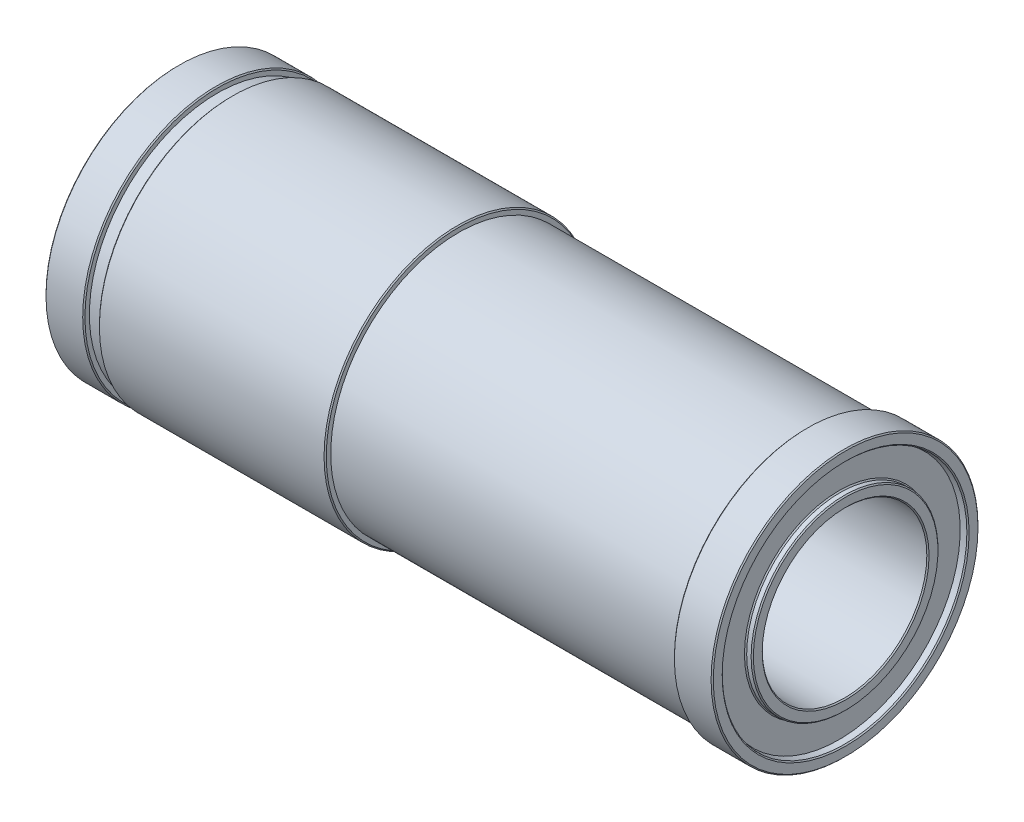
SolidWorks part; units mm, degrees
ref_plane "Front" through (0, 0, 0) normal (0, 0, 1) x (1, 0, 0)
ref_plane "Top" through (0, 0, 0) normal (0, 1, 0) x (1, 0, 0)
ref_plane "Right" through (0, 0, 0) normal (1, 0, 0) x (0, 0, -1)
sketch "Эскиз3" plane through (0, 0, 0) normal (0, 0, 1) x (1, 0, 0)
  line L0 (25.2, 8.9) -> (25.1, 9)
  line L1 (25.1, 9) -> (4.9, 9)
  line L2 (4.9, 9) -> (4.8, 8.9)
  line L3 (4.8, 8.9) -> (4.8, 8.5)
  line L4 (4.8, 8.5) -> (3.5, 8.5)
  line L5 (3.5, 8.5) -> (3.5, 8.9)
  line L6 (3.5, 8.9) -> (3.4, 9)
  line L7 (3.4, 9) -> (0.1, 9)
  line L8 (0.1, 9) -> (0, 8.9)
  line L9 (0, 8.9) -> (0, 8)
  line L10 (0, 8) -> (59.9, 8)
  line L11 (59.9, 8) -> (60, 8.1)
  line L12 (60, 8.1) -> (60, 8.9)
  line L13 (60, 8.9) -> (59.9, 9)
  line L14 (59.9, 9) -> (56.6, 9)
  line L15 (56.6, 9) -> (56.5, 8.9)
  line L16 (56.5, 8.9) -> (56.5, 8.5)
  line L17 (56.5, 8.5) -> (25.2, 8.5)
  line L18 (25.2, 8.5) -> (25.2, 8.9)
  line L19 (0, -3) -> (30, -3) construction
revolve "Повернуть2" add sketch "Эскиз3" angle 360 about L19
sketch "Эскиз7" plane through (0, 0, 0) normal (0, 0, 1) x (1, 0, 0)
  line L3 (0, 4.5) -> (0, 5.3)
  line L15 (30, -3) -> (0, -3) construction
  line L16 (60, 5.3) -> (60, 4.5)
  line L17 (59.9, 5.4) -> (60, 5.3)
  line L18 (59.5, 5.4) -> (59.9, 5.4)
  line L19 (59.4, 5.5) -> (59.5, 5.4)
  line L20 (59.4, 7.9) -> (59.4, 5.5)
  line L21 (0.6, 7.9) -> (59.4, 7.9)
  line L22 (0.6, 5.5) -> (0.6, 7.9)
  line L23 (0.5, 5.4) -> (0.6, 5.5)
  line L24 (0.1, 5.4) -> (0.5, 5.4)
  line L25 (0, 5.3) -> (0.1, 5.4)
  line L26 (0.1, 4.4) -> (0, 4.5)
  line L27 (59.9, 4.4) -> (0.1, 4.4)
  line L28 (60, 4.5) -> (59.9, 4.4)
revolve "Повернуть3" add sketch "Эскиз7" angle 360 about L15
